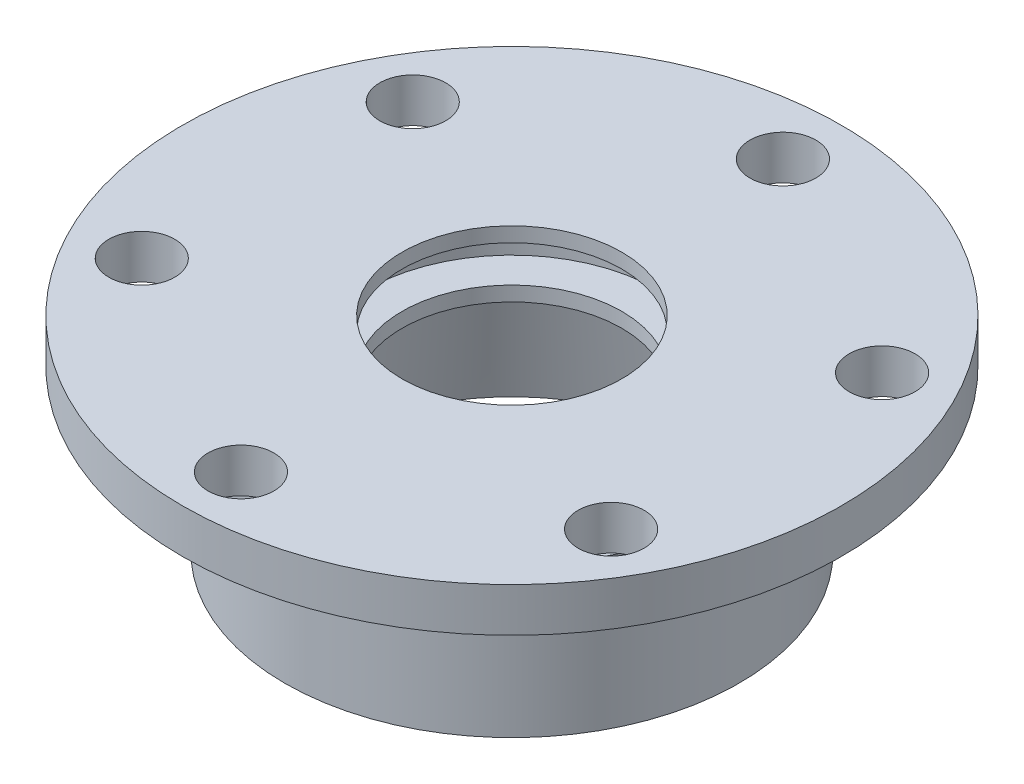
SolidWorks part; units mm, degrees
ref_plane "Front Plane" through (0, 0, 0) normal (0, 0, 1) x (1, 0, 0)
ref_plane "Top Plane" through (0, 0, 0) normal (0, 1, 0) x (1, 0, 0)
ref_plane "Right Plane" through (0, 0, 0) normal (1, 0, 0) x (0, 0, -1)
sketch "Sketch1" plane through (0, 0, 0) normal (0, 0, 1) x (1, 0, 0)
  line L0 (0, 30.6188) -> (0, -35.2308) construction
  line L2 (-45, 28) -> (-45, 22)
  line L3 (-45, 22) -> (-29.5, 22)
  line L4 (-29.5, 22) -> (-29.5, 20.5)
  line L5 (-29.5, 20.5) -> (-31, 20.5)
  line L6 (-31, 20.5) -> (-31, 0)
  line L7 (-31, 0) -> (-26, 0)
  line L8 (-26, 0) -> (-22.6498, 19)
  line L11 (-45, 28) -> (-29, 28)
  line L15 (-29, 28) -> (-15, 28)
  line L16 (-15, 28) -> (-15, 26)
  line L17 (-15, 26) -> (-20, 26)
  line L18 (-20, 26) -> (-20, 21)
  line L19 (-20, 21) -> (-15, 21)
  line L20 (-15, 21) -> (-15, 19)
  line L21 (-15, 19) -> (-22.6498, 19)
  dimension "D1" = 31
  dimension "D3" = 5
  dimension "D4" = 100
  dimension "D5" = 1.5
  dimension "D6" = 15.5
  dimension "D7" = 1.5
  dimension "D8" = 22
  dimension "D9" = 5
  dimension "D10" = 2
  dimension "D11" = 2
  dimension "D12" = 6
  dimension "D13" = 5
  dimension "D14" = 15
revolve "Revolve1" add sketch "Sketch1" angle 360 about L0
sketch "Sketch2" plane through (0, 28, 0) normal (0, 1, 0) x (1, 0, 0)
  line L0 (-53.4517, 0) -> (69.7526, 0) construction
  line L1 (0, 51.0634) -> (0, -55.84) construction
  circle A0 centre (0, 37) radius 4.5
  circle A1 centre (32.0429, 18.5) radius 4.5
  circle A2 centre (32.0429, -18.5) radius 4.5
  circle A3 centre (0, -37) radius 4.5
  circle A4 centre (-32.0429, -18.5) radius 4.5
  circle A5 centre (-32.0429, 18.5) radius 4.5
  point P19 (0, 0)
  dimension "D1" = 9
  dimension "D2" = 37
  dimension "D3" = 6
extrude "Cut-Extrude1" cut sketch "Sketch2" against normal up to next
